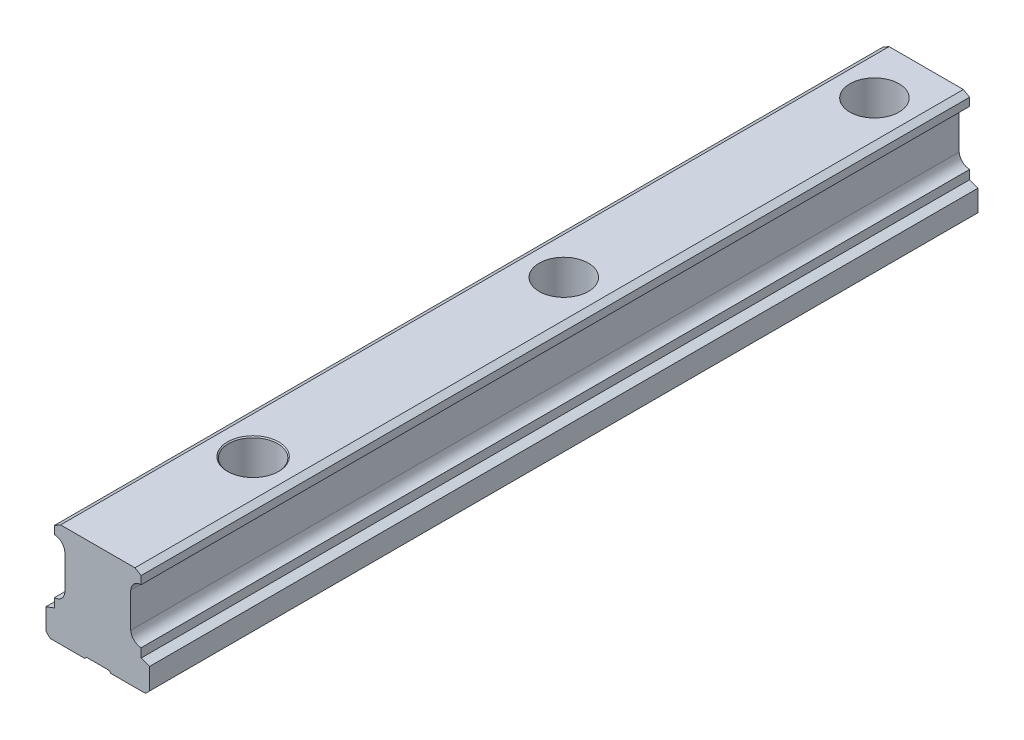
SolidWorks part; units mm, degrees
ref_plane "Plan de face" through (0, 0, 0) normal (0, 0, 1) x (1, 0, 0)
ref_plane "Plan de dessus" through (0, 0, 0) normal (0, 1, 0) x (1, 0, 0)
ref_plane "Plan de droite" through (0, 0, 0) normal (1, 0, 0) x (0, 0, -1)
ref_plane "Plan1" through (0, 0, 0) normal (0, 0, -1) x (-1, 0, 0)
sketch "Esquisse1" plane through (0, 0, 0) normal (0, 0, -1) x (-1, 0, 0)
  line L0 (-19.2, 7.9737) -> (-19.2, 0)
  line L1 (-19.2, 0) -> (0.8, 0)
  line L2 (0.8, 0) -> (0.8, 20)
  line L3 (0.8, 20) -> (-17.575, 20)
  line L4 (-17.575, 20) -> (-17.575, 17.7671)
  line L5 (-15.5625, 15.8524) -> (-15.5625, 9.1476)
  arc A0 (-15.5625, 9.1476) -> (-19.2, 7.9737) centre (-17.6174, 9.2924) cw
  arc A1 (-17.575, 17.7671) -> (-15.5625, 15.8524) centre (-17.6174, 15.7076) cw
extrude "Boss.-Extru.1" add sketch "Esquisse1" against normal blind 1980
sketch "Esquisse2" plane through (0, 0, 1980) normal (0, 0, 1) x (1, 0, 0)
  line L0 (17.575, 7.2329) -> (17.575, 4.9085)
  line L1 (17.575, 4.9085) -> (19.2, 4.9085)
  line L2 (19.2, 4.9085) -> (19.2, 7.9737)
  arc A0 (19.2, 7.9737) -> (17.575, 7.2329) centre (17.6174, 9.2924) cw
extrude "Enlèv. mat.-Extru.1" cut sketch "Esquisse2" against normal through all
sketch "Esquisse3" plane through (0, 0, 1980) normal (0, 0, 1) x (1, 0, 0)
  line L0 (7.05, 0) -> (11.35, 0)
  line L1 (11.35, 0) -> (11.35, 0.35)
  line L2 (11.35, 0.35) -> (7.05, 0.35)
  line L3 (7.05, 0.35) -> (7.05, 0)
extrude "Enlèv. mat.-Extru.2" cut sketch "Esquisse3" against normal blind 1980
sketch "Esquisse4" plane through (0, 0, 1980) normal (0, 0, 1) x (1, 0, 0)
  line L0 (-0.8, 5.5) -> (0.825, 5.5)
  line L1 (0.825, 5.5) -> (0.825, 20)
  line L2 (0.825, 20) -> (-0.8, 20)
  line L3 (-0.8, 20) -> (-0.8, 5.5)
extrude "Enlèv. mat.-Extru.3" cut sketch "Esquisse4" against normal through all
sketch "Esquisse5" plane through (0, 0, 1980) normal (0, 0, 1) x (1, 0, 0)
  line L0 (0.825, 17.7671) -> (0.825, 7.2329)
  line L1 (2.8375, 9.1476) -> (2.8375, 15.8524)
  arc A0 (0.825, 7.2329) -> (2.8375, 9.1476) centre (0.7826, 9.2924) ccw
  arc A1 (2.8375, 15.8524) -> (0.825, 17.7671) centre (0.7826, 15.7076) ccw
extrude "Enlèv. mat.-Extru.4" cut sketch "Esquisse5" against normal through all
draft "Dépouille1" type of draft neutral plane draft angle 20 faces to draft 1 face at (0.0125, 5.5, 990) neutral plane through (0.825, 5.5, 0) neutral plane normal (-1, 0, 0) parameters "D1"=20
draft "Dépouille2" type of draft neutral plane draft angle 20 faces to draft 1 face at (18.3875, 4.9085, 990) neutral plane through (19.2, 7.9737, 1980) neutral plane normal (1, 0, 0) parameters "D1"=20
draft "Dépouille3" type of draft neutral plane draft angle 45 faces to draft 2 face at (11.35, 0.175, 990) face at (7.05, 0.175, 990) neutral plane through (11.35, 0.35, 0) neutral plane normal (0, -1, 0) parameters "D1"=45
hole_wizard "Perçage1" positions "Esquisse7" profile "Esquisse6" legacy
sketch "Esquisse7" plane through (0, 20, 0) normal (0, 1, 0) x (1, 0, 0)
  point P0 (9.2, -30)
  point P1 (9.2, -90)
  point P2 (9.2, -150)
  point P3 (9.2, -210)
  point P4 (9.2, -270)
  point P5 (9.2, -330)
  point P6 (9.2, -390)
  point P7 (9.2, -450)
  point P8 (9.2, -510)
  point P9 (9.2, -570)
  point P10 (9.2, -630)
  point P11 (9.2, -690)
  point P12 (9.2, -750)
  point P13 (9.2, -810)
  point P14 (9.2, -870)
  point P15 (9.2, -930)
  point P16 (9.2, -990)
  point P17 (9.2, -1050)
  point P18 (9.2, -1110)
  point P19 (9.2, -1170)
  point P20 (9.2, -1230)
  point P21 (9.2, -1290)
  point P22 (9.2, -1350)
  point P23 (9.2, -1410)
  point P24 (9.2, -1470)
  point P25 (9.2, -1530)
  point P26 (9.2, -1590)
  point P27 (9.2, -1650)
  point P28 (9.2, -1710)
  point P29 (9.2, -1770)
  point P30 (9.2, -1830)
  point P31 (9.2, -1890)
  point P32 (9.2, -1950)
sketch "Esquisse6" plane through (9.2, 20, 30) normal (1, 0, 0) x (0, 0, 1)
  line L0 (0, 0) -> (0, 20)
  line L1 (0, 20) -> (3, 20)
  line L2 (3, 20) -> (3, 8.5)
  line L3 (3, 8.5) -> (4.75, 8.5)
  line L4 (4.75, 8.5) -> (4.75, 0)
  line L5 (4.75, 0) -> (0, 0)
  line L6 (0, 110) -> (0, -10) construction
  dimension "Diamètre" = 6
  dimension "Profondeur" = 20
  dimension "Diamètre chambrage" = 9.5
  dimension "Profondeur chambrage" = 8.5
chamfer "Chanfrein1" distance 0.8 angle 45 2 edges at (19.2, 0, 990) (-0.8, 0, 990)
chamfer "Chanfrein2" distance 1.2 angle 30 1 edges at (0.825, 20, 990)
chamfer "Chanfrein3" distance 0.2 angle 45 3 edges at (12.2, 0, 1950) (6.2, 0, 1950) (9.2, 20, 1954.75)
chamfer "Chanfrein4" distance 0.6928 angle 60 1 edges at (17.575, 20, 990)
ref_plane "Plan2" through (0, 0, 1980) normal (0, 0, 1) x (1, 0, 0)
sketch "Esquisse12" plane through (0, 0, 1980) normal (0, 0, 1) x (1, 0, 0)
  line L0 (-23.2139, 45.9286) -> (54.94, 45.9286)
  line L1 (-23.2139, 45.9286) -> (-23.2139, -28.586)
  line L2 (-23.2139, -28.586) -> (54.94, -28.586)
  line L3 (54.94, 45.9286) -> (54.94, -28.586)
extrude "Enlèv. mat.-Extru.5" cut sketch "Esquisse12" against normal through all from offset 160
